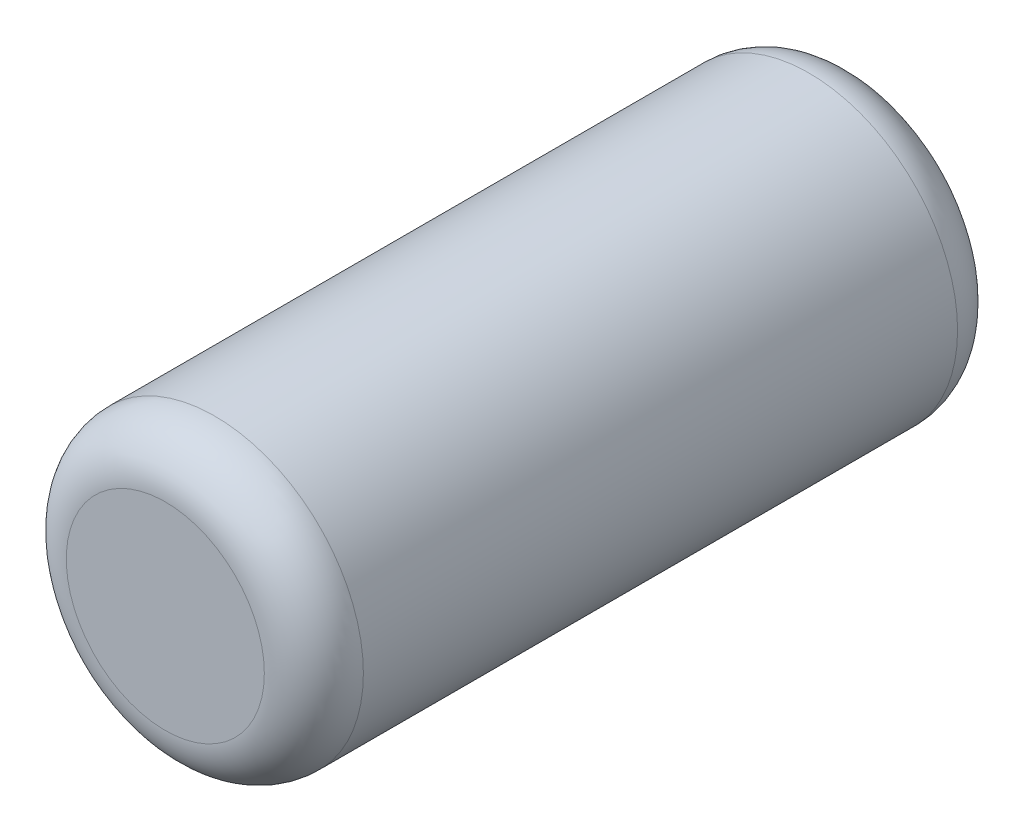
SolidWorks part; units mm, degrees
ref_plane "前视基准面" through (0, 0, 0) normal (0, 0, 1) x (1, 0, 0)
ref_plane "上视基准面" through (0, 0, 0) normal (0, 1, 0) x (1, 0, 0)
ref_plane "右视基准面" through (0, 0, 0) normal (1, 0, 0) x (0, 0, -1)
sketch "草图1" plane through (0, 0, 0) normal (0, 0, 1) x (1, 0, 0)
  circle A0 centre (0, 0) radius 1.5
  dimension "D1" = 3
extrude "凸台-拉伸1" add sketch "草图1" along normal blind 7
fillet "圆角1" radius 0.5 2 edges at (1.5, 0, 0) (1.5, 0, 7)
